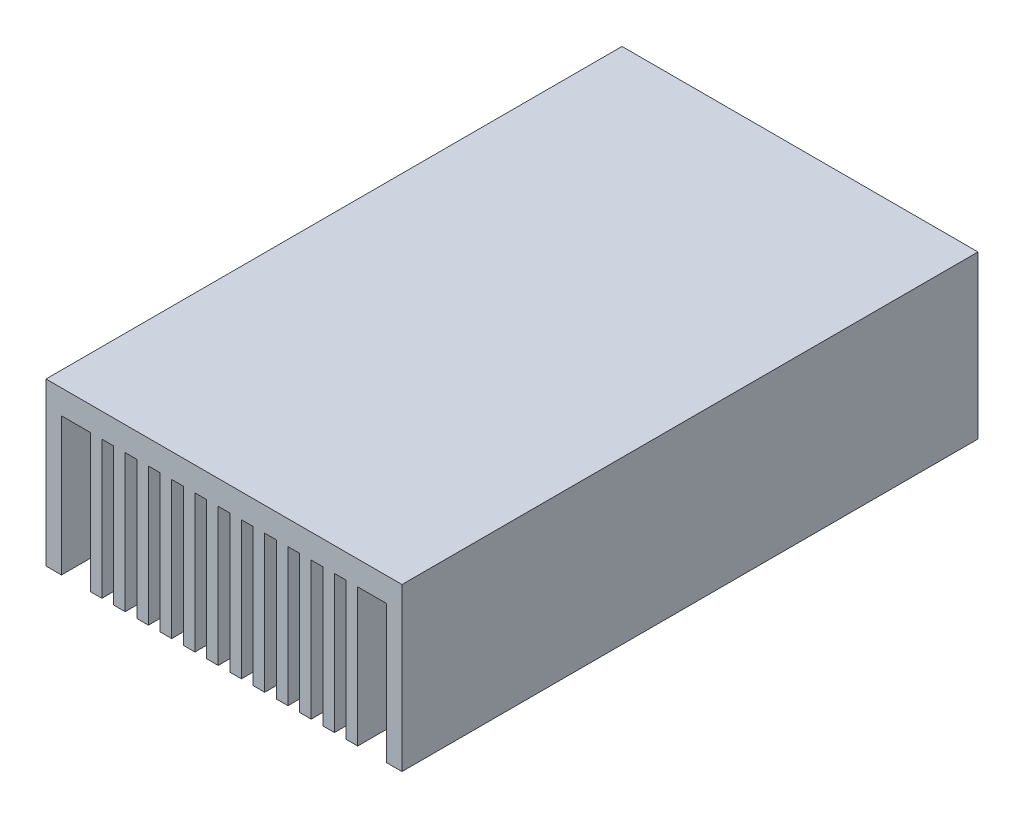
SolidWorks part; units mm, degrees
ref_plane "Front Plane" through (0, 0, 0) normal (0, 0, 1) x (1, 0, 0)
ref_plane "Top Plane" through (0, 0, 0) normal (0, 1, 0) x (1, 0, 0)
ref_plane "Right Plane" through (0, 0, 0) normal (1, 0, 0) x (0, 0, -1)
sketch "Sketch1" plane through (0, 0, 0) normal (0, 0, 1) x (1, 0, 0)
  line L0 (-49.44, -45) -> (-49.44, 0)
  line L1 (-49.44, 0) -> (49.44, 0)
  line L2 (49.44, 0) -> (49.44, -45)
  line L3 (49.44, -45) -> (45.14, -45)
  line L4 (45.14, -45) -> (45.14, -6.71)
  line L5 (45.14, -6.71) -> (37.14, -6.71)
  line L6 (37.14, -45) -> (37.14, -6.71)
  line L7 (37.14, -45) -> (-37.14, -45)
  line L8 (-37.14, -45) -> (-37.14, -6.71)
  line L9 (-37.14, -6.71) -> (-45.14, -6.71)
  line L10 (-45.14, -6.71) -> (-45.14, -45)
  line L11 (-45.14, -45) -> (-49.44, -45)
  dimension "D1" = 45
  dimension "D2" = 4.3
  dimension "D3" = 8
  dimension "D4" = 6.71
  dimension "D5" = 98.88
extrude "Boss-Extrude1" add sketch "Sketch1" against normal blind 160
sketch "Sketch4" plane through (0, 0, 0) normal (0, 0, 1) x (1, 0, 0)
  line L0 (-37.14, -45) -> (37.14, -45) construction
  line L1 (-33.9104, -6.71) -> (-30.6809, -6.71)
  line L2 (-33.9104, -6.71) -> (-33.9104, -45)
  line L3 (-33.9104, -45) -> (-30.6809, -45)
  line L4 (-30.6809, -6.71) -> (-30.6809, -45)
  line L5 (-45.14, -6.71) -> (-37.14, -6.71) construction
  line L6 (-33.9104, -6.71) -> (-37.14, -6.71) construction
  line L7 (-30.6809, -6.71) -> (-27.4513, -6.71) construction
  line L8 (-27.4513, -6.71) -> (-24.2217, -6.71)
  line L9 (-27.4513, -6.71) -> (-27.4513, -45)
  line L10 (-27.4513, -45) -> (-24.2217, -45)
  line L11 (-24.2217, -6.71) -> (-24.2217, -45)
  line L12 (-20.9922, -6.71) -> (-17.7626, -6.71)
  line L13 (-20.9922, -6.71) -> (-20.9922, -45)
  line L14 (-20.9922, -45) -> (-17.7626, -45)
  line L15 (-17.7626, -6.71) -> (-17.7626, -45)
  line L16 (-14.533, -6.71) -> (-11.3035, -6.71)
  line L17 (-14.533, -6.71) -> (-14.533, -45)
  line L18 (-14.533, -45) -> (-11.3035, -45)
  line L19 (-11.3035, -6.71) -> (-11.3035, -45)
  line L20 (-8.0739, -6.71) -> (-4.8443, -6.71)
  line L21 (-8.0739, -6.71) -> (-8.0739, -45)
  line L22 (-8.0739, -45) -> (-4.8443, -45)
  line L23 (-4.8443, -6.71) -> (-4.8443, -45)
  line L24 (-1.6148, -6.71) -> (1.6148, -6.71)
  line L25 (-1.6148, -6.71) -> (-1.6148, -45)
  line L26 (-1.6148, -45) -> (1.6148, -45)
  line L27 (1.6148, -6.71) -> (1.6148, -45)
  line L28 (-24.2217, -6.71) -> (-20.9922, -6.71) construction
  line L29 (-17.7626, -6.71) -> (-14.533, -6.71) construction
  line L30 (-11.3035, -6.71) -> (-8.0739, -6.71) construction
  line L31 (-4.8443, -6.71) -> (-1.6148, -6.71) construction
  line L32 (1.6148, -6.71) -> (4.8443, -6.71) construction
  line L33 (8.0739, -6.71) -> (11.3035, -6.71) construction
  line L34 (4.8443, -6.71) -> (8.0739, -6.71)
  line L35 (4.8443, -6.71) -> (4.8443, -45)
  line L36 (4.8443, -45) -> (8.0739, -45)
  line L37 (8.0739, -6.71) -> (8.0739, -45)
  line L38 (11.3035, -6.71) -> (14.533, -6.71)
  line L39 (11.3035, -6.71) -> (11.3035, -45)
  line L40 (11.3035, -45) -> (14.533, -45)
  line L41 (14.533, -6.71) -> (14.533, -45)
  line L42 (17.7626, -6.71) -> (20.9922, -6.71)
  line L43 (17.7626, -6.71) -> (17.7626, -45)
  line L44 (17.7626, -45) -> (20.9922, -45)
  line L45 (20.9922, -6.71) -> (20.9922, -45)
  line L46 (24.2217, -6.71) -> (27.4513, -6.71)
  line L47 (24.2217, -6.71) -> (24.2217, -45)
  line L48 (24.2217, -45) -> (27.4513, -45)
  line L49 (27.4513, -6.71) -> (27.4513, -45)
  line L50 (30.6809, -6.71) -> (33.9104, -6.71)
  line L51 (30.6809, -6.71) -> (30.6809, -45)
  line L52 (30.6809, -45) -> (33.9104, -45)
  line L53 (33.9104, -6.71) -> (33.9104, -45)
  line L54 (14.533, -6.71) -> (17.7626, -6.71) construction
  line L55 (20.9922, -6.71) -> (24.2217, -6.71) construction
  line L56 (27.4513, -6.71) -> (30.6809, -6.71) construction
  line L57 (33.9104, -6.71) -> (37.14, -6.71) construction
  line L58 (37.14, -45) -> (37.14, -6.71) construction
extrude "Cut-Extrude1" cut sketch "Sketch4" against normal through all
